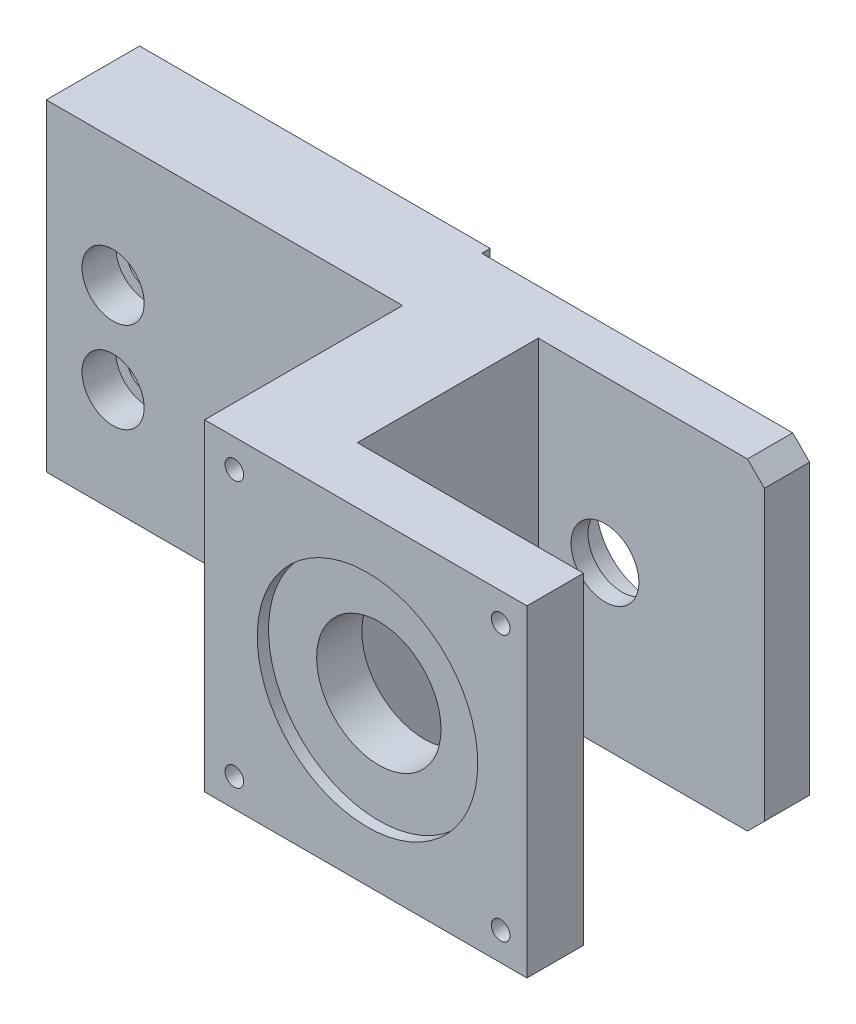
SolidWorks part; units mm, degrees
material "SKD11淬火HRC56-60"
ref_plane "前基準面" through (0, 0, 0) normal (0, 0, 1) x (1, 0, 0)
ref_plane "上基準面" through (0, 0, 0) normal (0, 1, 0) x (1, 0, 0)
ref_plane "右基準面" through (0, 0, 0) normal (1, 0, 0) x (0, 0, -1)
sketch "草图1" plane through (0, 0, 0) normal (0, 0, 1) x (1, 0, 0)
  line L1 (0, 0) -> (120, 0)
  line L2 (0, 0) -> (0, 57)
  line L3 (0, 57) -> (120, 57)
  line L4 (120, 0) -> (120, 57)
  dimension "D1" = 57
  dimension "D2" = 120
extrude "凸台-拉伸1" add sketch "草图1" along normal blind 50
sketch "草图2" plane through (0, 57, 0) normal (0, 1, 0) x (1, 0, 0)
  line L0 (120, -50) -> (120, 0) construction
  line L1 (120, -8) -> (80, -8)
  line L2 (120, -8) -> (120, -40)
  line L3 (120, -40) -> (80, -40)
  line L4 (80, -8) -> (80, -40)
  line L5 (120, 0) -> (0, 0) construction
  dimension "D1" = 8
  dimension "D2" = 32
  dimension "D3" = 40
extrude "切除-拉伸1" cut sketch "草图2" against normal through all
sketch "草图3" plane through (0, 57, 0) normal (0, 1, 0) x (-1, 0, 0)
  line L0 (-120, 0) -> (0, 0) construction
  line L1 (0, 50) -> (-63, 50)
  line L2 (0, 50) -> (0, 15)
  line L3 (0, 15) -> (-63, 15)
  line L4 (-63, 50) -> (-63, 15)
  line L5 (-120, 50) -> (-120, 40) construction
  dimension "D1" = 15
  dimension "D2" = 57
extrude "切除-拉伸2" cut sketch "草图3" against normal through all
sketch "草图4" plane through (0, 0, 0) normal (0, 0, -1) x (-1, 0, 0)
  line L0 (0, 0) -> (-120, 0) construction
  line L1 (0, 57) -> (-62, 57)
  line L2 (0, 57) -> (0, 0)
  line L3 (0, 0) -> (-62, 0)
  line L4 (-62, 57) -> (-62, 0)
  line L5 (-120, 0) -> (-120, 57) construction
  dimension "D1" = 58
extrude "凸台-拉伸2" add sketch "草图4" along normal blind 1.5
sketch "草图5" plane through (0, 0, 0) normal (0, 0, -1) x (-1, 0, 0)
  line L0 (-120, 28.5) -> (-66.6315, 28.5) construction
  line L1 (-120, 0) -> (-120, 57) construction
  circle A0 centre (-91.8, 28.5) radius 9.5
  dimension "D1" = 28.2
  dimension "D2" = 19
extrude "切除-拉伸3" cut sketch "草图5" against normal blind 5
sketch "草图6" plane through (0, 0, 5) normal (0, 0, -1) x (-1, 0, 0)
  circle A0 centre (-91.8, 28.5) radius 6
  dimension "D1" = 12
extrude "切除-拉伸4" cut sketch "草图6" against normal blind 20
sketch "草图7" plane through (0, 0, 40) normal (0, 0, -1) x (-1, 0, 0)
  circle A0 centre (-91.8, 28.5) radius 11
  dimension "D1" = 22
extrude "切除-拉伸5" cut sketch "草图7" against normal through all
chamfer "倒角1" distance 3 angle 45 2 edges at (120, 0, 4) (120, 57, 4)
sketch "草图8" plane through (0, 0, 50) normal (0, 0, 1) x (1, 0, 0)
  circle A0 centre (91.8, 28.5) radius 19.5
  dimension "D1" = 39
extrude "切除-拉伸6" cut sketch "草图8" against normal blind 2
hole_wizard "M6 六角凹头螺钉的柱形沉头孔1" positions "草图10" profile "草图9" counterbore size "M6" standard "ISO" end condition through all
sketch "草图10" plane through (0, 0, 15) normal (0, 0, 1) x (1, 0, 0)
  point P4 (11.8, 34.5)
  point P7 (11.8, 18.5)
  point P10 (51.8, 18.5)
  point P13 (51.8, 34.5)
sketch "草图9" plane through (11.8, 34.5, 15) normal (1, 0, 0) x (0, -1, 0)
  line L0 (0, 0) -> (0, 16.5)
  line L1 (0, 16.5) -> (3.5, 16.5)
  line L3 (3.5, 16.5) -> (3.5, 6)
  line L4 (3.5, 6) -> (5.5, 6)
  line L5 (5.5, 6) -> (5.5, 0)
  line L7 (5.5, 0) -> (0, 0)
  line L11 (0, -6.35) -> (0, 107.95) construction
  dimension "通孔孔直径" = 7
  dimension "通孔孔深度" = 16.5
  dimension "柱形沉头孔直径" = 11
  dimension "柱形沉头孔深度" = 6
hole_wizard "M4 螺纹孔1" positions "草图12" profile "草图11" tap size "M4" standard "ISO"
sketch "草图12" plane through (0, 0, 50) normal (0, 0, 1) x (1, 0, 0)
  point P0 (68.25, 52)
  point P4 (115.35, 5)
  point P10 (115.35, 52)
  point P13 (68.25, 5)
sketch "草图11" plane through (68.25, 52, 50) normal (1, 0, 0) x (0, -1, 0)
  line L0 (0, 0) -> (0, 11.0914)
  line L1 (0, 11.0914) -> (1.65, 10.1)
  line L2 (1.65, 10.1) -> (1.65, 0)
  line L5 (1.65, 0) -> (0, 0)
  line L10 (0, 11.0914) -> (-1.65, 10.1) construction
  line L11 (0, -6.35) -> (0, 107.95) construction
  dimension "螺纹孔钻头直径" = 3.3
  dimension "螺纹孔钻头深度" = 10.1
  dimension "导头角度" = 118
cosmetic thread "孔螺蚊线1" parameters "D1"=8, "D2"=4
cosmetic thread "孔螺蚊线2" parameters "D1"=8, "D2"=4
cosmetic thread "孔螺蚊线3" parameters "D1"=8, "D2"=4
cosmetic thread "孔螺蚊线4" parameters "D1"=8, "D2"=4
